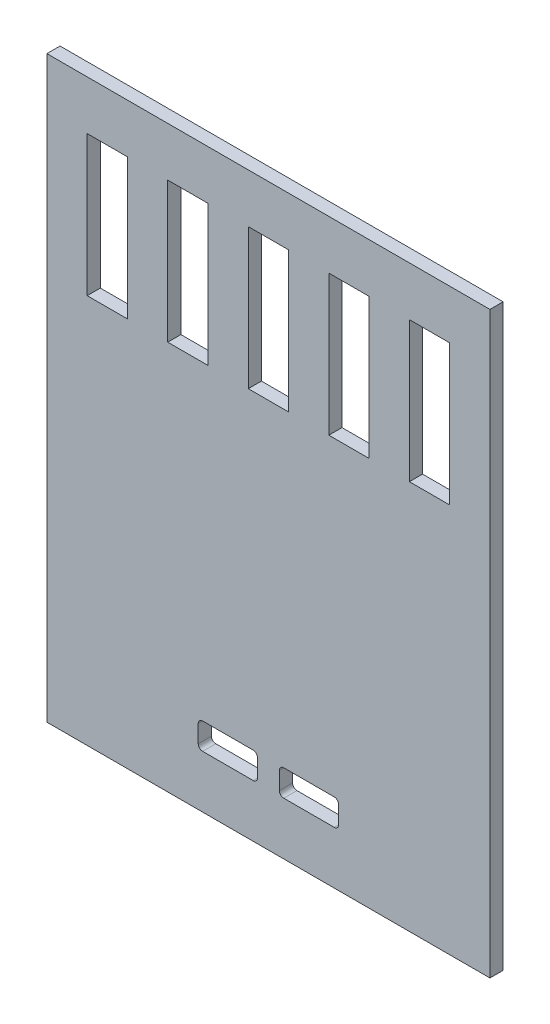
SolidWorks part; units mm, degrees
ref_plane "Front Plane" through (0, 0, 0) normal (0, 0, 1) x (1, 0, 0)
ref_plane "Top Plane" through (0, 0, 0) normal (0, 1, 0) x (1, 0, 0)
ref_plane "Right Plane" through (0, 0, 0) normal (1, 0, 0) x (0, 0, -1)
sketch "Sketch1" plane through (0, 0, 0) normal (0, 0, 1) x (1, 0, 0)
  line L1 (-50.5, -66) -> (50.5, -66)
  line L2 (-50.5, -66) -> (-50.5, 66)
  line L3 (-50.5, 66) -> (50.5, 66)
  line L4 (50.5, -66) -> (50.5, 66)
  line L5 (-50.5, -66) -> (50.5, 66) construction
  line L6 (-50.5, 66) -> (50.5, -66) construction
  point P0 (0, 0)
  dimension "D1" = 101
  dimension "D2" = 132
extrude "Boss-Extrude1" add sketch "Sketch1" along normal mid plane 3 contours L3 L4 L1 L2
sketch "Sketch2" plane through (0, 0, 1.5) normal (0, 0, 1) x (1, 0, 0)
  line L0 (3.5, -54) -> (15, -54)
  line L1 (-32.1364, 54.8) -> (-41.3182, 54.8)
  line L2 (-32.1364, 54.8) -> (-32.1364, 22.8)
  line L3 (-32.1364, 22.8) -> (-41.3182, 22.8)
  line L4 (-41.3182, 54.8) -> (-41.3182, 22.8)
  line L5 (-32.1364, 54.8) -> (-41.3182, 22.8) construction
  line L6 (-32.1364, 22.8) -> (-41.3182, 54.8) construction
  line L7 (-50.5, -66) -> (-50.5, 66) construction
  line L8 (-50.5, 66) -> (50.5, 66) construction
  line L9 (-13.7727, 54.8) -> (-22.9545, 54.8)
  line L10 (-13.7727, 54.8) -> (-13.7727, 22.8)
  line L11 (-13.7727, 22.8) -> (-22.9545, 22.8)
  line L12 (-22.9545, 54.8) -> (-22.9545, 22.8)
  line L13 (-13.7727, 54.8) -> (-22.9545, 22.8) construction
  line L14 (-13.7727, 22.8) -> (-22.9545, 54.8) construction
  line L15 (4.5909, 54.8) -> (-4.5909, 54.8)
  line L16 (4.5909, 54.8) -> (4.5909, 22.8)
  line L17 (4.5909, 22.8) -> (-4.5909, 22.8)
  line L18 (-4.5909, 54.8) -> (-4.5909, 22.8)
  line L19 (4.5909, 54.8) -> (-4.5909, 22.8) construction
  line L20 (4.5909, 22.8) -> (-4.5909, 54.8) construction
  line L21 (22.9545, 54.8) -> (13.7727, 54.8)
  line L22 (22.9545, 54.8) -> (22.9545, 22.8)
  line L23 (22.9545, 22.8) -> (13.7727, 22.8)
  line L24 (13.7727, 54.8) -> (13.7727, 22.8)
  line L25 (22.9545, 54.8) -> (13.7727, 22.8) construction
  line L26 (22.9545, 22.8) -> (13.7727, 54.8) construction
  line L27 (41.3182, 54.8) -> (32.1364, 54.8)
  line L28 (41.3182, 54.8) -> (41.3182, 22.8)
  line L29 (41.3182, 22.8) -> (32.1364, 22.8)
  line L30 (32.1364, 54.8) -> (32.1364, 22.8)
  line L31 (41.3182, 54.8) -> (32.1364, 22.8) construction
  line L32 (41.3182, 22.8) -> (32.1364, 54.8) construction
  line L33 (-9.25, -51) -> (9.25, -51) construction
  line L34 (-15, -54) -> (-3.5, -54)
  line L35 (-16, -53) -> (-16, -49)
  line L36 (-15, -48) -> (-3.5, -48)
  line L37 (-2.5, -53) -> (-2.5, -49)
  line L38 (2.5, -53) -> (2.5, -49)
  line L39 (3.5, -48) -> (15, -48)
  line L40 (16, -53) -> (16, -49)
  line L43 (-50.5, -66) -> (50.5, -66) construction
  arc A0 (-2.5, -49) -> (-3.5, -48) centre (-3.5, -49) ccw
  arc A1 (-3.5, -54) -> (-2.5, -53) centre (-3.5, -53) ccw
  arc A2 (-16, -53) -> (-15, -54) centre (-15, -53) ccw
  arc A3 (-16, -49) -> (-15, -48) centre (-15, -49) cw
  arc A4 (16, -49) -> (15, -48) centre (15, -49) ccw
  arc A5 (15, -54) -> (16, -53) centre (15, -53) ccw
  arc A6 (2.5, -53) -> (3.5, -54) centre (3.5, -53) ccw
  arc A7 (2.5, -49) -> (3.5, -48) centre (3.5, -49) cw
  point P0 (-36.7273, 38.8)
  point P11 (-18.3636, 38.8)
  point P16 (0, 38.8)
  point P21 (18.3636, 38.8)
  point P26 (36.7273, 38.8)
  point P33 (-9.25, -51)
  point P46 (9.25, -51)
  dimension "D7" = 1
  dimension "D8" = 1
  dimension "D1" = 9.1818
  dimension "D2" = 32
  dimension "D3" = 9.1818
  dimension "D4" = 11.2
  dimension "D6" = 32
  dimension "D9" = 5
  dimension "D10" = 15
  dimension "D11" = 13.5
  dimension "D12" = 6
  dimension "D13" = 13.5
  dimension "D14" = 6
  dimension "D15" = 6.75
  dimension "D16" = 41.25
  dimension "D17" = 3
  dimension "D18" = 6.75
  dimension "D19" = 3
  dimension "D5" = 5
extrude "Cut-Extrude1" cut sketch "Sketch2" against normal through all
sketch "Sketch3" plane through (0, 0, 1.5) normal (0, 0, 1) x (1, 0, 0)
  line L0 (0, 22.8) -> (0, -66) construction
  line L1 (-40, -41.2) -> (40, -41.2)
  line L2 (-40, -41.2) -> (-40, 6.8)
  line L3 (-40, 6.8) -> (40, 6.8)
  line L4 (40, -41.2) -> (40, 6.8)
  line L5 (-40, -41.2) -> (40, 6.8) construction
  line L6 (-40, 6.8) -> (40, -41.2) construction
  line L7 (-4.5909, 22.8) -> (4.5909, 22.8) construction
  line L8 (-50.5, -66) -> (50.5, -66) construction
  point P0 (0, -17.2)
  dimension "D1" = 80
  dimension "D2" = 48
  dimension "D3" = 40
  dimension "D4" = 16
